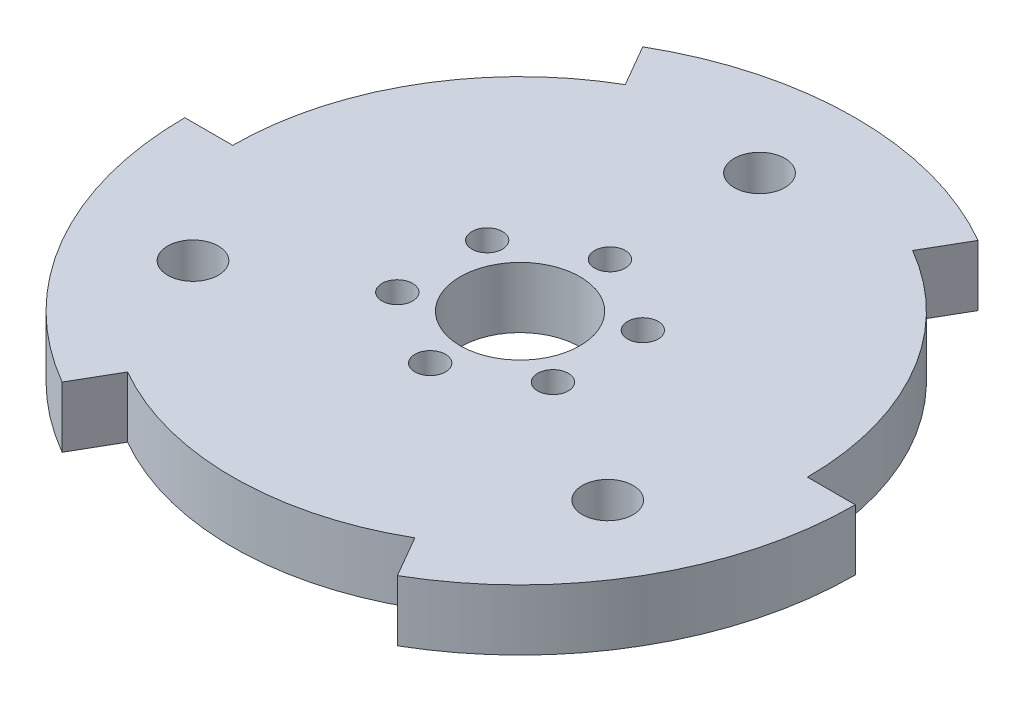
SolidWorks part; units mm, degrees
ref_plane "Front Plane" through (0, 0, 0) normal (0, 0, 1) x (1, 0, 0)
ref_plane "Top Plane" through (0, 0, 0) normal (0, 1, 0) x (1, 0, 0)
ref_plane "Right Plane" through (0, 0, 0) normal (1, 0, 0) x (0, 0, -1)
sketch "Baseplate Sketch" plane through (0, 0, 0) normal (0, 1, 0) x (1, 0, 0)
  line L0 (0, 0) -> (0, 61.4504) construction
  line L1 (-17.5, 30.3109) -> (-15, 25.9808)
  line L2 (17.5, 30.3109) -> (15, 25.9808)
  line L3 (-17.5, 30.3109) -> (-21.8301, 27.8109) construction
  line L4 (17.5, 30.3109) -> (13.1699, 32.8109) construction
  line L5 (17.5, -30.3109) -> (15, -25.9808)
  line L6 (35, 0) -> (30, 0)
  line L7 (-35, 0) -> (-30, 0)
  line L8 (-17.5, -30.3109) -> (-15, -25.9808)
  circle A0 centre (0, 0) radius 30
  circle A1 centre (0, 0) radius 6.25
  arc A2 (-17.5, 30.3109) -> (17.5, 30.3109) centre (0, 0) cw
  arc A3 (35, 0) -> (17.5, -30.3109) centre (0, 0) cw
  arc A4 (-17.5, -30.3109) -> (-35, 0) centre (0, 0) cw
  circle A5 centre (0, 25) radius 2.65
  circle A6 centre (21.6506, -12.5) radius 2.65
  circle A7 centre (-21.6506, -12.5) radius 2.65
  point P15 (0, 35)
  point P25 (0, 0)
  point P31 (0, 0)
  dimension "D1" = 60
  dimension "D2" = 12.5
  dimension "D3" = 35
  dimension "D4" = 90
  dimension "D5" = 5
  dimension "D12" = 5.3
  dimension "D6" = 5
  dimension "D7" = 90
  dimension "D8" = 60
  dimension "D9" = 5
  dimension "D10" = 5
  dimension "D14" = 25
  dimension "D11" = 3
  dimension "D13" = 3
extrude "Boss-Extrude1" add sketch "Baseplate Sketch" along normal blind 6.35 contours A4 L8 A0 L7 | A3 L6 A0 L5 | A2 L1 A0 L2 | A1 | A6 | A7 | A5
ref_plane "Plane1" [suppressed] through (0, 0, 40) normal (0, 0, 1) x (1, 0, 0)
sketch "Sketch2" [suppressed] plane through (0, 0, 40) normal (0, 0, 1) x (1, 0, 0)
  line L0 (0, 6.35) -> (0, 0) construction
  line L4 (15, 6.35) -> (-15, 6.35)
  line L5 (-15, 6.35) -> (-15, 0)
  line L6 (-15, 0) -> (15, 0)
  line L7 (15, 0) -> (15, 6.35)
  line L8 (15, 6.35) -> (-15, 6.35) construction
  line L9 (-15, 6.35) -> (-15, 0) construction
  line L10 (-15, 0) -> (15, 0) construction
  line L11 (15, 0) -> (15, 6.35) construction
  circle A0 centre (0, 3.175) radius 2.25
  dimension "D1" = 0
  dimension "D2" = 4.5
extrude "Cut-Extrude1" [suppressed] cut sketch "Sketch2" against normal blind 25
pattern_circular "CirPattern1" [suppressed] count 3 over 360
sketch "Sketch3" plane through (0, 6.35, 0) normal (0, 1, 0) x (1, 0, 0)
  circle A2 centre (-8.1276, -4.6925) radius 1.6
  circle A5 centre (0, -9.385) radius 1.6
  circle A6 centre (-8.1276, 4.6925) radius 1.6
  circle A7 centre (0, 9.385) radius 1.6
  circle A8 centre (8.1276, 4.6925) radius 1.6
  circle A9 centre (8.1276, -4.6925) radius 1.6
  point P14 (0, 0)
  dimension "D1" = 3.2
  dimension "D2" = 9.385
  dimension "D3" = 9.385
extrude "Cut-Extrude2" cut sketch "Sketch3" against normal up to surface (6.35 mm away)
